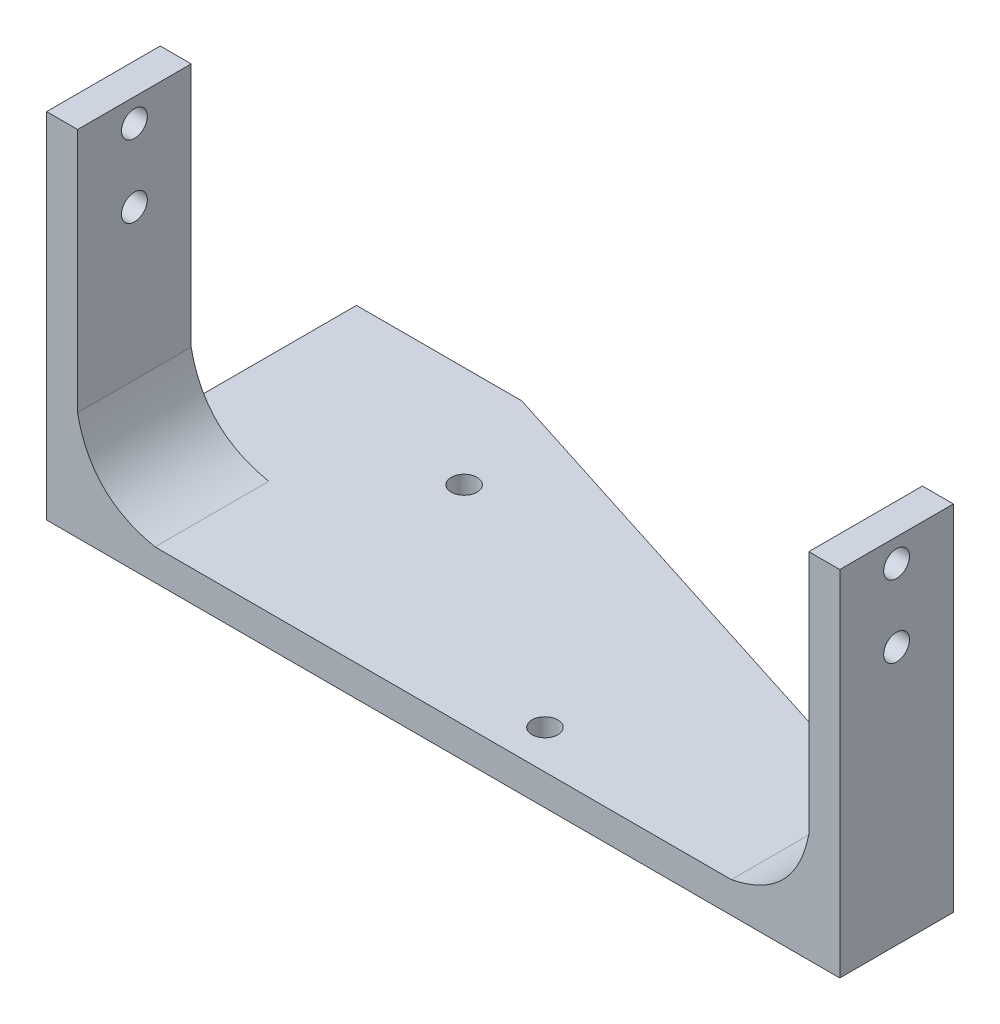
SolidWorks part; units mm, degrees
ref_plane "Front Plane" through (0, 0, 0) normal (0, 0, 1) x (1, 0, 0)
ref_plane "Top Plane" through (0, 0, 0) normal (0, 1, 0) x (1, 0, 0)
ref_plane "Right Plane" through (0, 0, 0) normal (1, 0, 0) x (0, 0, -1)
sketch "Sketch1" plane through (0, 0, 0) normal (0, 1, 0) x (1, 0, 0)
  line L0 (32, 60) -> (151.12, 22)
  line L1 (0, 0) -> (151.12, 0)
  line L2 (0, 0) -> (0, 60)
  line L5 (32, 60) -> (0, 60)
  line L6 (151.12, 0) -> (151.12, 22)
  circle A0 centre (40.5, 40.35) radius 2.5
  circle A1 centre (89, 7.5) radius 2.5
  dimension "D4" = 5
  dimension "D5" = 5
  dimension "D8" = 89
  dimension "D2" = 32.85
  dimension "D3" = 40.5
  dimension "D6" = 60
  dimension "D7" = 7.5
  dimension "D15" = 22
  dimension "D16" = 32
  dimension "D17" = 151.12
extrude "Boss-Extrude1" add sketch "Sketch1" along normal blind 6
sketch "Sketch2" plane through (0, 6, 0) normal (0, 1, 0) x (1, 0, 0)
  line L1 (0, 0) -> (6, 0)
  line L2 (0, 0) -> (0, 22)
  line L3 (0, 22) -> (6, 22)
  line L4 (6, 0) -> (6, 22)
  dimension "D1" = 6
  dimension "D2" = 22
extrude "Boss-Extrude2" add sketch "Sketch2" along normal blind 62.5
sketch "Sketch3" plane through (0, 0, 0) normal (-1, 0, 0) x (0, 0, 1)
  line L0 (-22, 68.5) -> (0, 68.5) construction
  line L1 (0, 68.5) -> (0, 0) construction
  line L2 (-22, 68.5) -> (-22, 6) construction
  circle A0 centre (-11, 64) radius 2.5
  circle A1 centre (-11, 50) radius 2.5
  dimension "D1" = 5
  dimension "D2" = 5
  dimension "D3" = 14
  dimension "D4" = 4.5
  dimension "D5" = 11
  dimension "D6" = 11
sketch "Sketch4" plane through (0, 6, 0) normal (0, 1, 0) x (1, 0, 0)
  line L0 (6, 0) -> (151.12, 0) construction
  line L1 (147.5895, 22) -> (153.5895, 22)
  line L2 (147.5895, 22) -> (147.5895, 0)
  line L3 (147.5895, 0) -> (153.5895, 0)
  line L4 (153.5895, 22) -> (153.5895, 0)
  line L5 (151.12, 0) -> (151.12, 22) construction
  dimension "D1" = 6
  dimension "D2" = 0
  dimension "D3" = 22
  dimension "D4" = 3.5305
extrude "Boss-Extrude3" add sketch "Sketch4" along normal up to surface and the other way up to surface up to face at (3, 68.5, -11) other way up to face at (66.848, 0, -28.4)
extrude "Cut-Extrude2" cut sketch "Sketch3" against normal through all
sketch "Sketch5" plane through (0, 0, 0) normal (0, 0, 1) x (1, 0, 0)
  line L0 (6, 68.5) -> (6, 6) construction
  line L1 (6, 6) -> (147.5895, 6) construction
  line L2 (6, 21) -> (6, 6)
  line L3 (6, 6) -> (21, 6)
  line L4 (147.5895, 68.5) -> (147.5895, 6) construction
  line L5 (132.5895, 6) -> (147.5895, 6)
  line L6 (147.5895, 6) -> (147.5895, 21)
  spline S0 degree 2 poles (6, 21) (8.5, 8.5) (21, 6) knots 0 0 0 1 1 1
  spline S1 degree 2 poles (147.5895, 21) (145.0895, 8.5) (132.5895, 6) knots 0 0 0 1 1 1
  dimension "D3" = 5
  dimension "D1" = 15
  dimension "D2" = 15
  dimension "D4" = 5
  dimension "D5" = 15
  dimension "D6" = 15
  dimension "D7" = 5
  dimension "D8" = 5
extrude "Boss-Extrude4" add sketch "Sketch5" against normal up to surface (22 mm away) up to face at (3, 37.25, -22)
